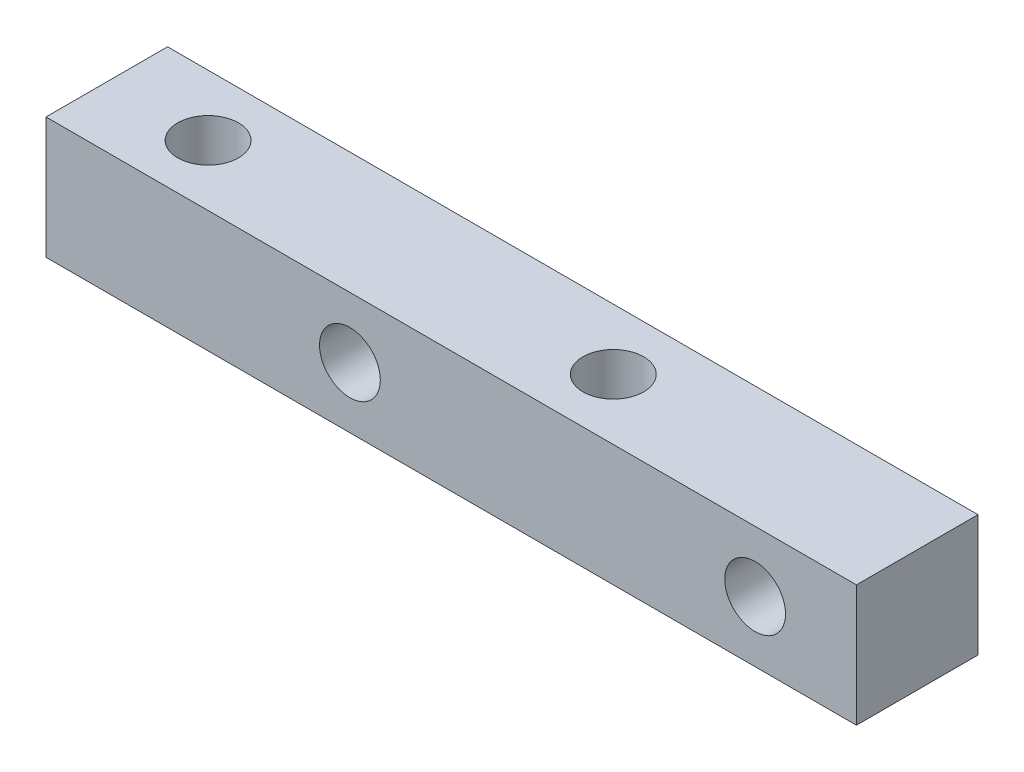
SolidWorks part; units mm, degrees
ref_plane "前视基准面" through (0, 0, 0) normal (0, 0, 1) x (1, 0, 0)
ref_plane "上视基准面" through (0, 0, 0) normal (0, 1, 0) x (1, 0, 0)
ref_plane "右视基准面" through (0, 0, 0) normal (1, 0, 0) x (0, 0, -1)
other "Configuration Table"
sketch "草图1" plane through (0, 0, 0) normal (0, 0, 1) x (1, 0, 0)
  line L1 (-20, 3) -> (20, 3)
  line L2 (-20, 3) -> (-20, -3)
  line L3 (-20, -3) -> (20, -3)
  line L4 (20, 3) -> (20, -3)
  line L5 (0, -3) -> (0, 3) construction
  line L6 (-20, 0) -> (20, 0) construction
  point P0 (0, 0)
  dimension "D1" = 40
  dimension "D2" = 6
extrude "凸台-拉伸1" add sketch "草图1" along normal blind 6
sketch "草图2" plane through (0, 3, 0) normal (0, 1, 0) x (1, 0, 0)
  line L0 (-20, -3) -> (20, -3) construction
  line L1 (-20, -6) -> (-20, 0) construction
  line L2 (20, -6) -> (20, 0) construction
  circle A0 centre (-15, -3) radius 1.5
  circle A1 centre (5, -3) radius 1.5
  point P10 (0, 0)
  dimension "D1" = 3
  dimension "D2" = 3
  dimension "D3" = 5
  dimension "D4" = 15
extrude "切除-拉伸1" cut sketch "草图2" against normal blind 6
sketch "草图3" plane through (0, 0, 6) normal (0, 0, 1) x (1, 0, 0)
  line L0 (-20, 0) -> (20, 0) construction
  line L3 (-20, 3) -> (-20, -3) construction
  line L4 (20, -3) -> (20, 3) construction
  circle A0 centre (-5, 0) radius 1.5
  circle A1 centre (15, 0) radius 1.5
  point P6 (-20, 0)
  point P10 (0, 0)
  point P12 (20, 0)
  dimension "D1" = 3
  dimension "D2" = 3
  dimension "D3" = 15
  dimension "D4" = 5
extrude "切除-拉伸2" cut sketch "草图3" against normal blind 6
